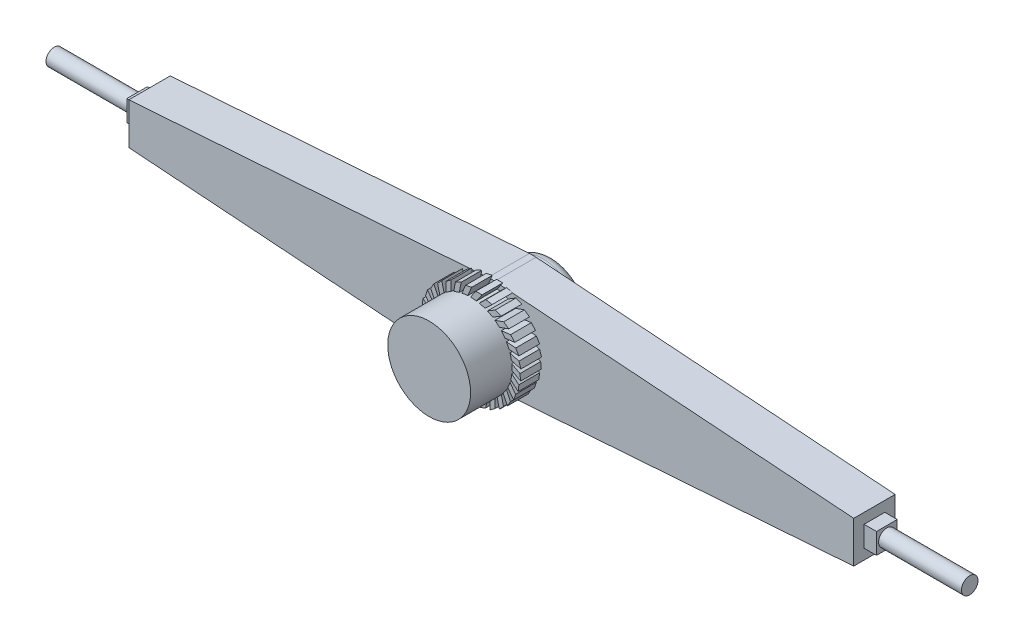
SolidWorks part; units mm, degrees
ref_plane "Ön Düzlem" through (0, 0, 0) normal (0, 0, 1) x (1, 0, 0)
ref_plane "Üst Düzlem" through (0, 0, 0) normal (0, 1, 0) x (1, 0, 0)
ref_plane "Sağ Düzlem" through (0, 0, 0) normal (1, 0, 0) x (0, 0, -1)
sketch "Sketch1" plane through (0, 0, 0) normal (0, 0, 1) x (1, 0, 0)
  line L0 (-175, 0) -> (175, 0) construction
  line L1 (0, -25.1429) -> (0, 26.8571) construction
  line L2 (-175, -10) -> (-175, 10)
  line L3 (-175, 10) -> (-1.6104, 22.4423)
  line L4 (-175, -10) -> (-1.6104, -22.4423)
  line L5 (175, -10) -> (1.6104, -22.4423)
  line L6 (175, -10) -> (175, 10)
  line L7 (175, 10) -> (1.6104, 22.4423)
  arc A0 (-1.6104, -22.4423) -> (1.6104, -22.4423) centre (0, 0) ccw
  arc A1 (1.6104, 22.4423) -> (-1.6104, 22.4423) centre (0, 0) ccw
  dimension "D3" = 45
  dimension "D1" = 20
  dimension "D2" = 350
extrude "Boss-Extrude1" add sketch "Sketch1" along normal mid plane 20
sketch "Sketch2" plane through (0, 0, 10) normal (0, 0, 1) x (1, 0, 0)
  circle A0 centre (0, 0) radius 20
  dimension "D1" = 40
extrude "Boss-Extrude2" add sketch "Sketch2" along normal blind 30
sketch "Sketch3" plane through (0, 0, -10) normal (0, 0, -1) x (-1, 0, 0)
  circle A0 centre (0, 0) radius 18.5
  dimension "D1" = 37
extrude "Boss-Extrude3" add sketch "Sketch3" along normal blind 10
fillet "Fillet1" radius 5 1 edges at (-18.5, 0, -20)
sketch "Sketch4" plane through (175, 0, 0) normal (1, 0, 0) x (0, 0, -1)
  line L1 (5, 5) -> (-5, 5)
  line L2 (5, 5) -> (5, -5)
  line L3 (5, -5) -> (-5, -5)
  line L4 (-5, 5) -> (-5, -5)
  line L5 (5, 5) -> (-5, -5) construction
  line L6 (5, -5) -> (-5, 5) construction
  point P0 (0, 0)
  dimension "D1" = 10
  dimension "D2" = 10
extrude "Boss-Extrude4" add sketch "Sketch4" along normal blind 6
sketch "Sketch5" plane through (181, 0, 0) normal (1, 0, 0) x (0, 0, -1)
  circle A0 centre (0, 0) radius 4
  dimension "D1" = 8
extrude "Boss-Extrude5" add sketch "Sketch5" along normal blind 40
mirror "Mirror1" about plane through (0, 0, 0) normal (1, 0, 0) of "Boss-Extrude5", "Boss-Extrude4"
sketch "Sketch6" plane through (0, 0, 10) normal (0, 0, 1) x (1, 0, 0)
  line L0 (0, 20) -> (0, -20) construction
  line L1 (-20, 0) -> (20, 0) construction
  line L2 (0, -20) -> (-2.5521, -23.7063)
  line L3 (-2.5521, -23.7063) -> (-5.5521, -23.7063)
  line L4 (-5.5521, -23.7063) -> (-2.8586, -19.7947)
  line L5 (-10.3596, -22.034) -> (-6.9117, -18.7678)
  line L6 (-4.1582, -19.563) -> (-7.4251, -22.6577)
  line L7 (-7.4251, -22.6577) -> (-10.3596, -22.034)
  line L8 (-14.7143, -19.3986) -> (-10.6627, -16.9206)
  line L9 (-8.1347, -18.2709) -> (-11.9737, -20.6188)
  line L10 (-11.9737, -20.6188) -> (-14.7143, -19.3986)
  line L11 (-18.426, -15.9154) -> (-13.9477, -14.334)
  line L12 (-11.7557, -16.1803) -> (-15.9989, -17.6788)
  line L13 (-15.9989, -17.6788) -> (-18.426, -15.9154)
  line L14 (-21.3323, -11.7367) -> (-16.6231, -11.1209)
  line L15 (-14.8629, -13.3826) -> (-19.3249, -13.9661)
  line L16 (-19.3249, -13.9661) -> (-21.3323, -11.7367)
  line L17 (-23.3063, -7.0449) -> (-18.572, -7.4217)
  line L18 (-17.3205, -10) -> (-21.8063, -9.643)
  line L19 (-21.8063, -9.643) -> (-23.3063, -7.0449)
  line L20 (-24.2618, -2.0453) -> (-19.7092, -3.3982)
  line L21 (-19.0211, -6.1803) -> (-23.3347, -4.8985)
  line L22 (-23.3347, -4.8985) -> (-24.2618, -2.0453)
  line L23 (-24.1568, 3.0437) -> (-19.985, 0.7738)
  line L24 (-19.8904, -2.0906) -> (-23.8432, 0.0601)
  line L25 (-23.8432, 0.0601) -> (-24.1568, 3.0437)
  line L26 (-22.9961, 7.9996) -> (-19.3874, 4.9121)
  line L27 (-19.8904, 2.0906) -> (-23.3097, 5.0161)
  line L28 (-23.3097, 5.0161) -> (-22.9961, 7.9996)
  line L29 (-20.8304, 12.606) -> (-17.9425, 8.8356)
  line L30 (-19.0211, 6.1803) -> (-21.7574, 9.7528)
  line L31 (-21.7574, 9.7528) -> (-20.8304, 12.606)
  line L32 (-17.7543, 16.6614) -> (-15.7134, 12.373)
  line L33 (-17.3205, 10) -> (-19.2543, 14.0633)
  line L34 (-19.2543, 14.0633) -> (-17.7543, 16.6614)
  line L35 (-13.9022, 19.9886) -> (-12.7975, 15.3696)
  line L36 (-14.8629, 13.3826) -> (-15.9096, 17.7592)
  line L37 (-15.9096, 17.7592) -> (-13.9022, 19.9886)
  line L38 (-9.4425, 22.4423) -> (-9.3223, 17.6945)
  line L39 (-11.7557, 16.1803) -> (-11.8696, 20.6789)
  line L40 (-11.8696, 20.6789) -> (-9.4425, 22.4423)
  line L41 (-4.5702, 23.915) -> (-5.4397, 19.246)
  line L42 (-8.1347, 18.2709) -> (-7.3108, 22.6948)
  line L43 (-7.3108, 22.6948) -> (-4.5702, 23.915)
  line L44 (0.5019, 24.3426) -> (-1.3194, 19.9564)
  line L45 (-4.1582, 19.563) -> (-2.4325, 23.7189)
  line L46 (-2.4325, 23.7189) -> (0.5019, 24.3426)
  line L47 (5.5521, 23.7063) -> (2.8586, 19.7947)
  line L48 (0, 20) -> (2.5521, 23.7063)
  line L49 (2.5521, 23.7063) -> (5.5521, 23.7063)
  line L50 (10.3596, 22.034) -> (6.9117, 18.7678)
  line L51 (4.1582, 19.563) -> (7.4251, 22.6577)
  line L52 (7.4251, 22.6577) -> (10.3596, 22.034)
  line L53 (14.7143, 19.3986) -> (10.6627, 16.9206)
  line L54 (8.1347, 18.2709) -> (11.9737, 20.6188)
  line L55 (11.9737, 20.6188) -> (14.7143, 19.3986)
  line L56 (18.426, 15.9154) -> (13.9477, 14.334)
  line L57 (11.7557, 16.1803) -> (15.9989, 17.6788)
  line L58 (15.9989, 17.6788) -> (18.426, 15.9154)
  line L59 (21.3323, 11.7367) -> (16.6231, 11.1209)
  line L60 (14.8629, 13.3826) -> (19.3249, 13.9661)
  line L61 (19.3249, 13.9661) -> (21.3323, 11.7367)
  line L62 (23.3063, 7.0449) -> (18.572, 7.4217)
  line L63 (17.3205, 10) -> (21.8063, 9.643)
  line L64 (21.8063, 9.643) -> (23.3063, 7.0449)
  line L65 (24.2618, 2.0453) -> (19.7092, 3.3982)
  line L66 (19.0211, 6.1803) -> (23.3347, 4.8985)
  line L67 (23.3347, 4.8985) -> (24.2618, 2.0453)
  line L68 (24.1568, -3.0437) -> (19.985, -0.7738)
  line L69 (19.8904, 2.0906) -> (23.8432, -0.0601)
  line L70 (23.8432, -0.0601) -> (24.1568, -3.0437)
  line L71 (22.9961, -7.9996) -> (19.3874, -4.9121)
  line L72 (19.8904, -2.0906) -> (23.3097, -5.0161)
  line L73 (23.3097, -5.0161) -> (22.9961, -7.9996)
  line L74 (20.8304, -12.606) -> (17.9425, -8.8356)
  line L75 (19.0211, -6.1803) -> (21.7574, -9.7528)
  line L76 (21.7574, -9.7528) -> (20.8304, -12.606)
  line L77 (17.7543, -16.6614) -> (15.7134, -12.373)
  line L78 (17.3205, -10) -> (19.2543, -14.0633)
  line L79 (19.2543, -14.0633) -> (17.7543, -16.6614)
  line L80 (13.9022, -19.9886) -> (12.7975, -15.3696)
  line L81 (14.8629, -13.3826) -> (15.9096, -17.7592)
  line L82 (15.9096, -17.7592) -> (13.9022, -19.9886)
  line L83 (9.4425, -22.4423) -> (9.3223, -17.6945)
  line L84 (11.7557, -16.1803) -> (11.8696, -20.6789)
  line L85 (11.8696, -20.6789) -> (9.4425, -22.4423)
  line L86 (4.5702, -23.915) -> (5.4397, -19.246)
  line L87 (8.1347, -18.2709) -> (7.3108, -22.6948)
  line L88 (7.3108, -22.6948) -> (4.5702, -23.915)
  line L89 (-0.5019, -24.3426) -> (1.3194, -19.9564)
  line L90 (4.1582, -19.563) -> (2.4325, -23.7189)
  line L91 (2.4325, -23.7189) -> (-0.5019, -24.3426)
  circle A2 centre (0, 0) radius 20
  circle A3 centre (0, 0) radius 20 construction
  arc A4 (-2.8586, -19.7947) -> (0, -20) centre (0, 0) ccw
  arc A5 (-6.9117, -18.7678) -> (-4.1582, -19.563) centre (0, 0) ccw
  circle A6 centre (0, 0) radius 20 construction
  arc A7 (-10.6627, -16.9206) -> (-8.1347, -18.2709) centre (0, 0) ccw
  circle A8 centre (0, 0) radius 20 construction
  arc A9 (-13.9477, -14.334) -> (-11.7557, -16.1803) centre (0, 0) ccw
  circle A10 centre (0, 0) radius 20 construction
  arc A11 (-16.6231, -11.1209) -> (-14.8629, -13.3826) centre (0, 0) ccw
  circle A12 centre (0, 0) radius 20 construction
  arc A13 (-18.572, -7.4217) -> (-17.3205, -10) centre (0, 0) ccw
  circle A14 centre (0, 0) radius 20 construction
  arc A15 (-19.7092, -3.3982) -> (-19.0211, -6.1803) centre (0, 0) ccw
  circle A16 centre (0, 0) radius 20 construction
  arc A17 (-19.985, 0.7738) -> (-19.8904, -2.0906) centre (0, 0) ccw
  circle A18 centre (0, 0) radius 20 construction
  arc A19 (-19.3874, 4.9121) -> (-19.8904, 2.0906) centre (0, 0) ccw
  circle A20 centre (0, 0) radius 20 construction
  arc A21 (-17.9425, 8.8356) -> (-19.0211, 6.1803) centre (0, 0) ccw
  circle A22 centre (0, 0) radius 20 construction
  arc A23 (-15.7134, 12.373) -> (-17.3205, 10) centre (0, 0) ccw
  circle A24 centre (0, 0) radius 20 construction
  arc A25 (-12.7975, 15.3696) -> (-14.8629, 13.3826) centre (0, 0) ccw
  circle A26 centre (0, 0) radius 20 construction
  arc A27 (-9.3223, 17.6945) -> (-11.7557, 16.1803) centre (0, 0) ccw
  circle A28 centre (0, 0) radius 20 construction
  arc A29 (-5.4397, 19.246) -> (-8.1347, 18.2709) centre (0, 0) ccw
  circle A30 centre (0, 0) radius 20 construction
  arc A31 (-1.3194, 19.9564) -> (-4.1582, 19.563) centre (0, 0) ccw
  circle A32 centre (0, 0) radius 20 construction
  arc A33 (2.8586, 19.7947) -> (0, 20) centre (0, 0) ccw
  circle A34 centre (0, 0) radius 20 construction
  arc A35 (6.9117, 18.7678) -> (4.1582, 19.563) centre (0, 0) ccw
  circle A36 centre (0, 0) radius 20 construction
  arc A37 (10.6627, 16.9206) -> (8.1347, 18.2709) centre (0, 0) ccw
  circle A38 centre (0, 0) radius 20 construction
  arc A39 (13.9477, 14.334) -> (11.7557, 16.1803) centre (0, 0) ccw
  circle A40 centre (0, 0) radius 20 construction
  arc A41 (16.6231, 11.1209) -> (14.8629, 13.3826) centre (0, 0) ccw
  circle A42 centre (0, 0) radius 20 construction
  arc A43 (18.572, 7.4217) -> (17.3205, 10) centre (0, 0) ccw
  circle A44 centre (0, 0) radius 20 construction
  arc A45 (19.7092, 3.3982) -> (19.0211, 6.1803) centre (0, 0) ccw
  circle A46 centre (0, 0) radius 20 construction
  arc A47 (19.985, -0.7738) -> (19.8904, 2.0906) centre (0, 0) ccw
  circle A48 centre (0, 0) radius 20 construction
  arc A49 (19.3874, -4.9121) -> (19.8904, -2.0906) centre (0, 0) ccw
  circle A50 centre (0, 0) radius 20 construction
  arc A51 (17.9425, -8.8356) -> (19.0211, -6.1803) centre (0, 0) ccw
  circle A52 centre (0, 0) radius 20 construction
  arc A53 (15.7134, -12.373) -> (17.3205, -10) centre (0, 0) ccw
  circle A54 centre (0, 0) radius 20 construction
  arc A55 (12.7975, -15.3696) -> (14.8629, -13.3826) centre (0, 0) ccw
  circle A56 centre (0, 0) radius 20 construction
  arc A57 (9.3223, -17.6945) -> (11.7557, -16.1803) centre (0, 0) ccw
  circle A58 centre (0, 0) radius 20 construction
  arc A59 (5.4397, -19.246) -> (8.1347, -18.2709) centre (0, 0) ccw
  circle A60 centre (0, 0) radius 20 construction
  arc A61 (1.3194, -19.9564) -> (4.1582, -19.563) centre (0, 0) ccw
  circle A62 centre (0, 0) radius 20 construction
  dimension "D1" = 0
  dimension "D2" = 4.5
  dimension "D3" = 3
  dimension "D4" = 34.55
  dimension "D5" = 30
extrude "Boss-Extrude6" add sketch "Sketch6" along normal blind 10
